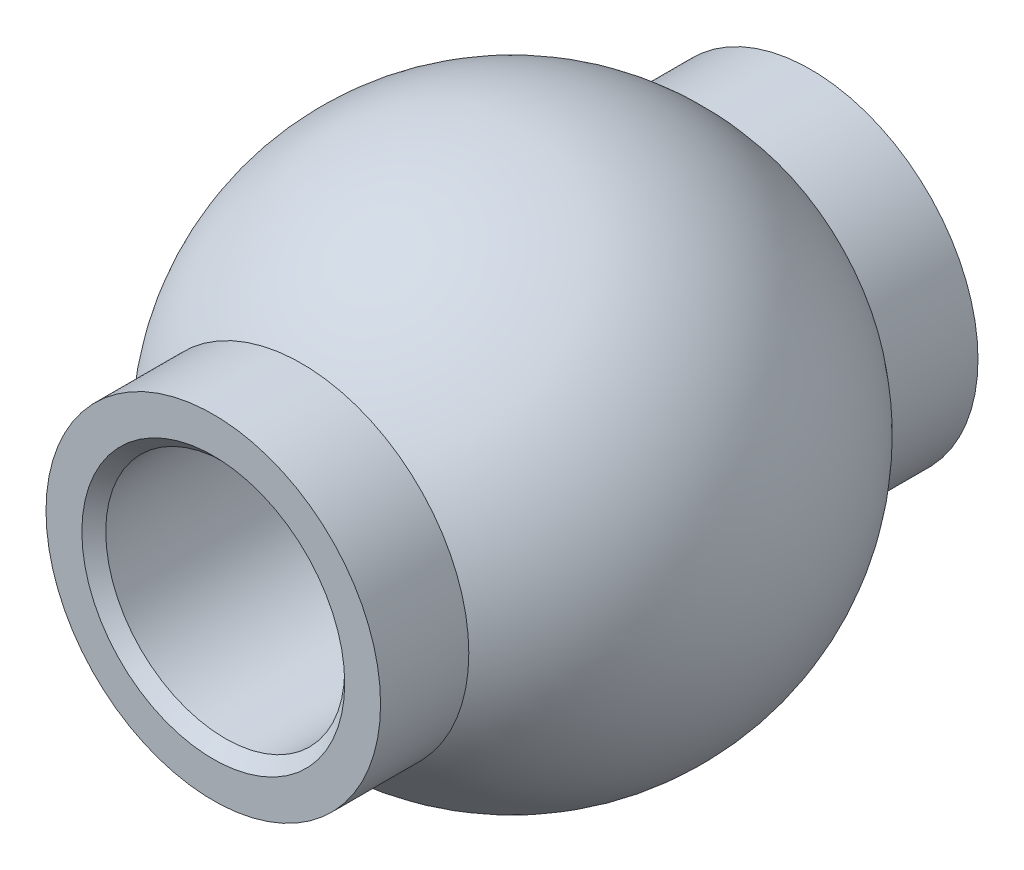
SolidWorks part; units mm, degrees
ref_plane "Front" through (0, 0, 0) normal (0, 0, 1) x (1, 0, 0)
ref_plane "Top" through (0, 0, 0) normal (0, 1, 0) x (1, 0, 0)
ref_plane "Right" through (0, 0, 0) normal (1, 0, 0) x (0, 0, -1)
sketch "Sketch1" plane through (0, 0, 0) normal (0, 0, 1) x (1, 0, 0)
  line L0 (0, 0) -> (0, -41.275)
  line L1 (0, -41.275) -> (6.35, -41.275)
  line L2 (6.35, -41.275) -> (6.35, 0)
  line L3 (6.35, 0) -> (0, 0)
  line L5 (0, 44.45) -> (0, 0) construction
  line L6 (0, 44.45) -> (19.05, 44.45) construction
  line L7 (19.05, 44.45) -> (19.05, 25.4) construction
  line L8 (-6.35, -41.275) -> (-6.35, 0) construction
  arc A0 (11.43, 10.16) -> (0, 44.45) centre (0, 25.4) ccw construction
  circle A1 centre (0, 25.4) radius 6.35 construction
  circle A2 centre (0, 25.4) radius 14.2875 construction
  circle A3 centre (0, 25.4) radius 15.0019 construction
  arc A4 (6.35, 0) -> (11.43, 10.16) centre (19.05, 0) cw construction
  point P16 (-6.35, -31.4325)
  dimension "A" = 12.7
  dimension "Ball Dia" = 28.575
  dimension "B" = 38.1
  dimension "D1" = 30.0038
  dimension "D" = 66.675
  dimension "E" = 41.275
  dimension "Thread Dia" = 12.7
  dimension "D2" = 9.8425
sketch "Sketch7" plane through (0, 0, 0) normal (0, 0, 1) x (1, 0, 0)
  line L0 (0, 39.6875) -> (0, 11.1125)
  line L1 (0, 44.45) -> (0, 0) construction
  line L2 (0, 0) -> (0, 11.1125) construction
  arc A0 (0, 11.1125) -> (0, 39.6875) centre (0, 25.4) ccw
  circle A1 centre (0, 25.4) radius 14.2875 construction
revolve "Revolve3" add sketch "Sketch7" angle 360 about L2
sketch "Sketch10" plane through (0, 0, 0) normal (0, 0, 1) x (1, 0, 0)
  circle A0 centre (0, 25.4) radius 6.35 construction
  circle A1 centre (0, 25.4) radius 6.35
extrude "Cut-Extrude4" cut sketch "Sketch10" against normal through all and the other way through all
sketch "Sketch12" plane through (0, 0, 0) normal (0, 0, 1) x (1, 0, 0)
  circle A0 centre (0, 25.4) radius 8.89
  circle A1 centre (0, 25.4) radius 6.35 construction
  circle A2 centre (0, 25.4) radius 6.35
  dimension "D1" = 17.78
extrude "Extrude1" add sketch "Sketch12" along normal mid plane 31.75
chamfer "Chamfer1" distance 0.635 angle 45 2 edges at (6.35, 25.4, -15.875) (6.35, 25.4, 15.875)
equation "\"D1@Sketch1\"=\"Ball Dia@Sketch1\"*1.05"
equation "\"D1@Sketch12\" = \"A@Sketch1\" * 1.4"
